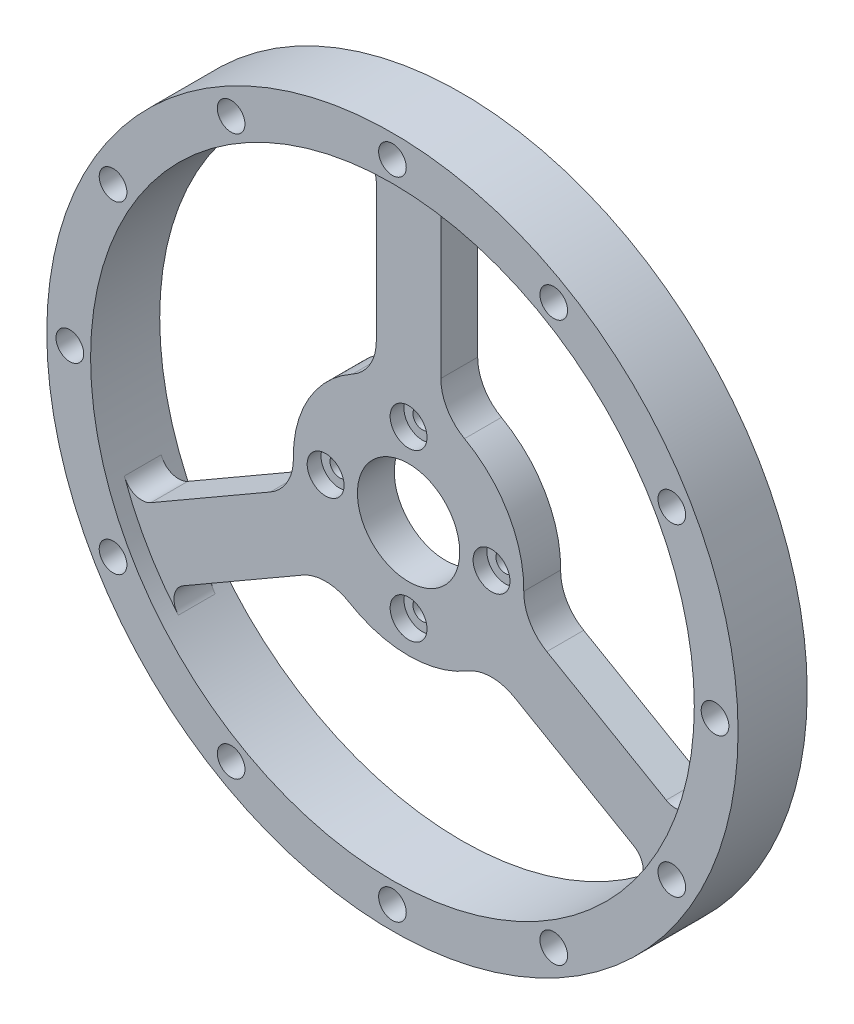
SolidWorks part; units mm, degrees
ref_plane "Front Plane" through (0, 0, 0) normal (0, 0, 1) x (1, 0, 0)
ref_plane "Top Plane" through (0, 0, 0) normal (0, 1, 0) x (1, 0, 0)
ref_plane "Right Plane" through (0, 0, 0) normal (1, 0, 0) x (0, 0, -1)
sketch "Sketch1" plane through (0, 0, 0) normal (0, 0, 1) x (1, 0, 0)
  circle A0 centre (0, 0) radius 75
  dimension "D1" = 150
extrude "Boss-Extrude1" add sketch "Sketch1" along normal blind 15
sketch "Sketch2" plane through (0, 0, 0) normal (0, 0, 1) x (1, 0, 0)
  circle A0 centre (0, 0) radius 65.5
  dimension "D1" = 131
extrude "Cut-Extrude1" cut sketch "Sketch2" along normal through all both
sketch "Sketch5" plane through (0, 0, 0) normal (0, 0, 1) x (1, 0, 0)
  circle A0 centre (0, 0) radius 25
  dimension "D1" = 50
extrude "Boss-Extrude3" add sketch "Sketch5" along normal blind 8 from offset 3.5
sketch "Sketch6" plane through (0, 0, 0) normal (0, 0, 1) x (1, 0, 0)
  line L0 (0, 0) -> (-73.8626, -42.6446) construction
  line L1 (0, 0) -> (69.4127, -40.0754) construction
  line L2 (0, -8.25) -> (0, 8.25) construction
  line L3 (-7, 24) -> (7, 24)
  line L4 (7, 24) -> (7, 69)
  line L5 (7, 69) -> (-7, 69)
  line L6 (-7, 69) -> (-7, 24)
  line L8 (17.2846, -18.0622) -> (56.2558, -40.5622)
  line L9 (56.2558, -40.5622) -> (63.2558, -28.4378)
  line L10 (63.2558, -28.4378) -> (24.2846, -5.9378)
  line L12 (24.2846, -5.9378) -> (17.2846, -18.0622)
  line L14 (-17.2846, -18.0622) -> (-56.2558, -40.5622)
  line L15 (-56.2558, -40.5622) -> (-63.2558, -28.4378)
  line L16 (-63.2558, -28.4378) -> (-24.2846, -5.9378)
  line L18 (-24.2846, -5.9378) -> (-17.2846, -18.0622)
  circle A0 centre (0, 0) radius 25 construction
  dimension "D1" = 120
  dimension "D2" = 120
  dimension "D3" = 45
  dimension "D4" = 45
  dimension "D5" = 45
  dimension "D6" = 14
  dimension "D7" = 14
  dimension "D8" = 14
  dimension "D9" = 7
  dimension "D10" = 7
  dimension "D11" = 7
extrude "Boss-Extrude4" add sketch "Sketch6" along normal blind 8 from offset 3.5
sketch "Sketch9" plane through (0, 0, 0) normal (0, 0, 1) x (1, 0, 0)
  circle A0 centre (0, 0) radius 11.1
  dimension "D1" = 22.2
extrude "Cut-Extrude4" cut sketch "Sketch9" along normal through all
sketch "Sketch10" plane through (0, 0, 0) normal (0, 0, 1) x (1, 0, 0)
  line L0 (0, -8.25) -> (0, 8.25) construction
  line L1 (8.25, 0) -> (-8.25, 0) construction
  circle A0 centre (0, 18) radius 2.05
  circle A1 centre (18, 0) radius 2.05
  circle A2 centre (0, -18) radius 2.05
  circle A3 centre (-18, 0) radius 2.05
  dimension "D5" = 4.1
  dimension "D1" = 18
  dimension "D2" = 18
  dimension "D3" = 18
  dimension "D4" = 18
extrude "Cut-Extrude5" cut sketch "Sketch10" along normal through all
fillet "Fillet3" radius 10 6 edges at (7, 24, 7.5) (24.2846, -5.9378, 7.5) (17.2846, -18.0622, 7.5) (-17.2846, -18.0622, 7.5) (-24.2846, -5.9378, 7.5) (-7, 24, 7.5)
sketch "Sketch11" plane through (0, 0, 0) normal (0, 0, 1) x (1, 0, 0)
  circle A0 centre (18, 0) radius 4
  circle A1 centre (0, -18) radius 4
  circle A2 centre (-18, 0) radius 4
  circle A3 centre (0, 18) radius 4
  dimension "D1" = 8
extrude "Cut-Extrude6" cut sketch "Sketch11" against normal blind 3 from surface
sketch "Sketch12" plane through (0, 0, 15) normal (0, 0, 1) x (1, 0, 0)
  line L0 (0, -8.25) -> (0, 8.25) construction
  circle A0 centre (0, 70) radius 3
  circle A1 centre (0, 0) radius 75 construction
  circle A2 centre (35, 60.6218) radius 3
  circle A3 centre (60.6218, 35) radius 3
  circle A4 centre (70, 0) radius 3
  circle A5 centre (60.6218, -35) radius 3
  circle A6 centre (35, -60.6218) radius 3
  circle A7 centre (0, -70) radius 3
  circle A8 centre (-35, -60.6218) radius 3
  circle A9 centre (-60.6218, -35) radius 3
  circle A10 centre (-70, 0) radius 3
  circle A11 centre (-60.6218, 35) radius 3
  circle A12 centre (-35, 60.6218) radius 3
  point P30 (0, 0)
  dimension "D1" = 6
  dimension "D2" = 70
  dimension "D3" = 12
extrude "Cut-Extrude7" cut sketch "Sketch12" against normal through all
fillet "Fillet4" radius 4 6 edges at (52.8998, -38.6246, 7.5) (59.8998, -26.5003, 7.5) (-52.8998, -38.6246, 7.5) (-59.8998, -26.5003, 7.5) (-7, 65.1249, 7.5) (7, 65.1249, 7.5)
